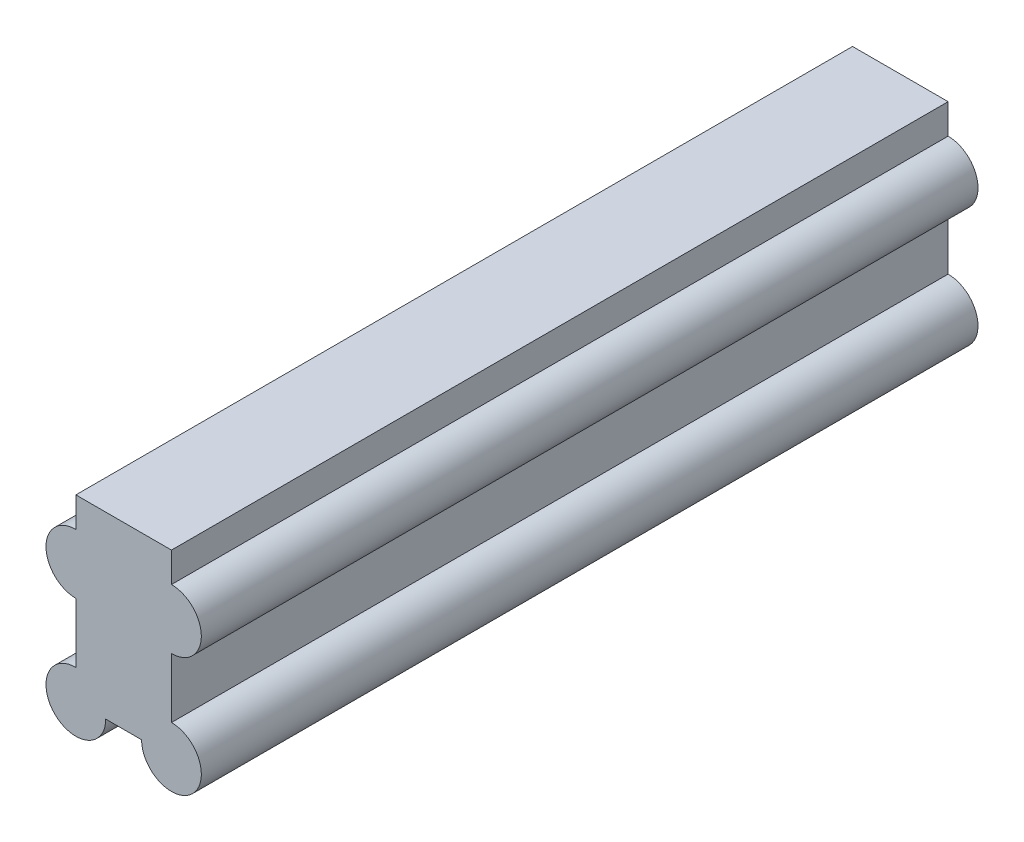
SolidWorks part; units mm, degrees
material "ABS"
ref_plane "Спереди" through (0, 0, 0) normal (0, 0, 1) x (1, 0, 0)
ref_plane "Сверху" through (0, 0, 0) normal (0, 1, 0) x (1, 0, 0)
ref_plane "Справа" through (0, 0, 0) normal (1, 0, 0) x (0, 0, -1)
sketch "Эскиз1" plane through (0, 0, 0) normal (0, 0, -1) x (1, 0, 0)
  line L0 (-39.4894, 0) -> (42.2128, 0) construction
  line L1 (8, -15) -> (-8, -15)
  line L2 (8, -15) -> (8, 15)
  line L3 (8, 15) -> (-8, 15)
  line L4 (-8, -15) -> (-8, 15)
  line L5 (8, -15) -> (-8, 15) construction
  line L6 (8, 15) -> (-8, -15) construction
  line L7 (0, 20.6443) -> (0, -13.1265) construction
  circle A0 centre (-8, -5) radius 5
  circle A1 centre (-8, 15) radius 5
  circle A2 centre (8, -5) radius 5
  circle A3 centre (8, 15) radius 5
  point P0 (0, 0)
  point P16 (0, 0)
  point P17 (8, -7.5225)
  dimension "D3" = 10
  dimension "D1" = 30
  dimension "D2" = 16
  dimension "D4" = 20
extrude "Бобышка-Вытянуть1" add sketch "Эскиз1" along normal mid plane 130 contours A0 L4 | A0 L4 | L3 A3 L2 A2 L1 L4 A0 A1 | A1 L4 L3 | A1 L3 L4 | A3 L2 L3 | A3 L3 L2 | A2 L2 | A2 L2
